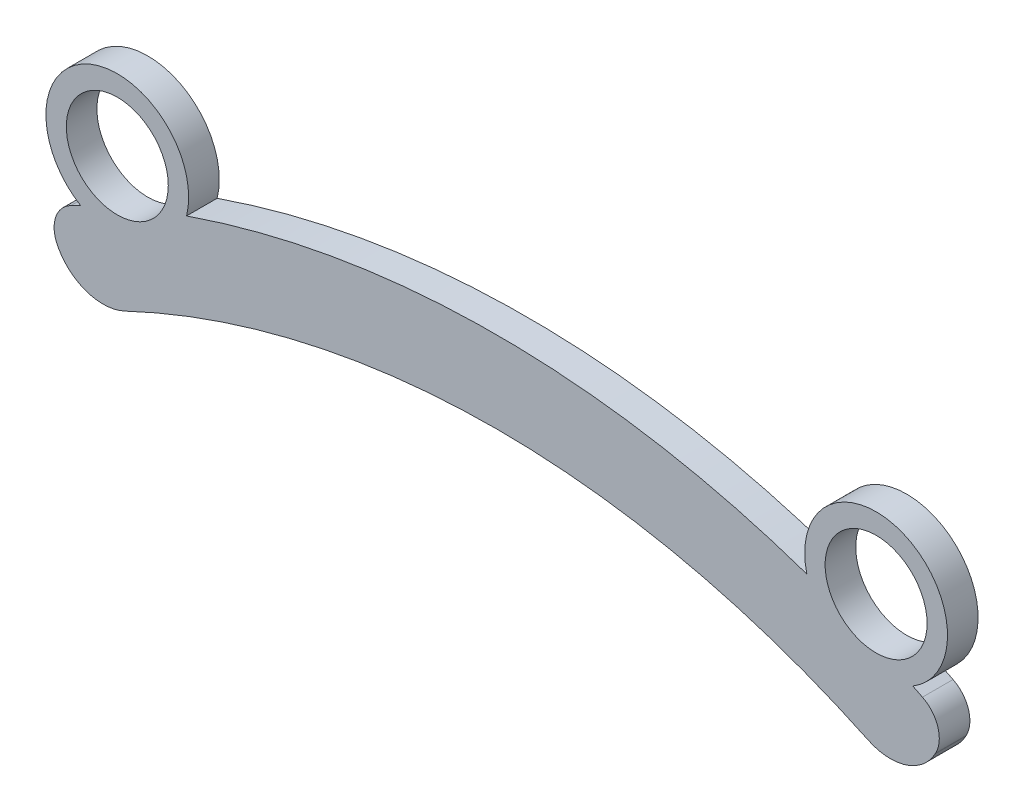
SolidWorks part; units mm, degrees
material "Galvanized Steel"
ref_plane "Front Plane" through (0, 0, 0) normal (0, 0, 1) x (1, 0, 0)
ref_plane "Top Plane" through (0, 0, 0) normal (0, 1, 0) x (1, 0, 0)
ref_plane "Right Plane" through (0, 0, 0) normal (1, 0, 0) x (0, 0, -1)
sketch "Sketch1" plane through (0, 0, 0) normal (0, 0, 1) x (1, 0, 0)
  line L0 (0, 0) -> (0, 49.3634)
  line L1 (-43.0413, 78.9838) -> (-42.9988, 78.9057)
  line L2 (43.0413, 78.9838) -> (42.9988, 78.9057)
  arc A0 (36.4634, 76.7816) -> (-36.4634, 76.7816) centre (0, 0) ccw
  arc A1 (41.754, 83.1) -> (38.3702, 84.7156) centre (0, 0) ccw
  arc A2 (40.8025, 83.5713) -> (30.4181, 87.8848) centre (37.21, 89.5791) ccw
  arc A4 (-40.8025, 83.5713) -> (-30.4181, 87.8848) centre (-37.21, 89.5791) cw
  arc A5 (43.0653, 79.0277) -> (-43.0653, 79.0277) centre (0, 0) ccw
  arc A6 (-42.9988, 78.9057) -> (-36.4634, 76.7816) centre (-38.6083, 81.2982) ccw
  arc A7 (36.4634, 76.7816) -> (42.9988, 78.9057) centre (38.6083, 81.2982) ccw
  arc A8 (-41.754, 83.1) -> (-43.0413, 78.9838) centre (-40.4071, 80.4193) ccw
  arc A9 (41.754, 83.1) -> (43.0413, 78.9838) centre (40.4071, 80.4193) cw
  circle A10 centre (-37.21, 89.5791) radius 5
  circle A11 centre (37.21, 89.5791) radius 5
  arc A12 (-38.3702, 84.7156) -> (-41.754, 83.1) centre (0, 0) ccw
  arc A13 (30.4181, 87.8848) -> (-32.9453, 86.969) centre (0, 0) ccw
  point P15 (-40.6728, 74.6373)
  point P18 (40.6728, 74.6373)
  point P21 (-44.5008, 81.662)
  point P24 (44.5008, 81.662)
  dimension "D1" = 170
  dimension "D2" = 186
  dimension "D4" = 14
  dimension "D5" = 180
  dimension "D6" = 5
  dimension "D7" = 3
  dimension "D8" = 10
  dimension "D9" = 10
  dimension "D3" = 74.42
extrude "Boss-Extrude1" add sketch "Sketch1" along normal blind 3
scale "Scale1" scale about centroid uniform scaling yes scale factor 3
